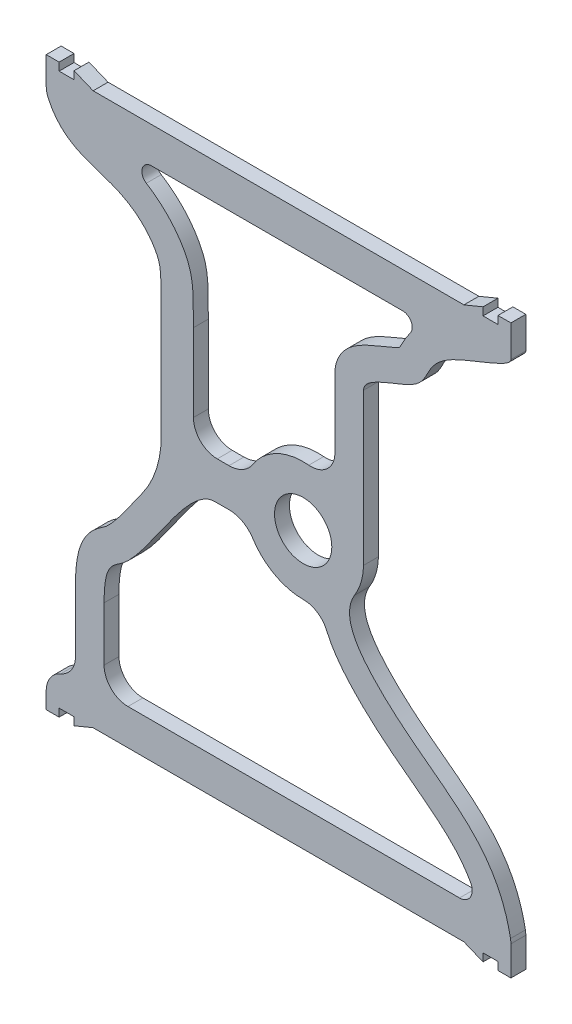
SolidWorks part; units mm, degrees
ref_plane "Front Plane" through (0, 0, 0) normal (0, 0, 1) x (1, 0, 0)
ref_plane "Top Plane" through (0, 0, 0) normal (0, 1, 0) x (1, 0, 0)
ref_plane "Right Plane" through (0, 0, 0) normal (1, 0, 0) x (0, 0, -1)
sketch "Sketch1" plane through (0, 0, 0) normal (0, 0, 1) x (1, 0, 0)
  line L0 (-41.684, 53.6194) -> (-41.684, 15.991) construction
  line L1 (-63.4451, 56.9953) -> (-61.4131, 56.1594)
  line L2 (-16.9595, 0) -> (-66.4086, 0) construction
  line L3 (-16.9595, 53.6194) -> (-16.9595, 56.9953)
  line L4 (-63.4451, 56.1594) -> (-63.4451, 56.9953)
  line L5 (-65.0326, 56.1594) -> (-65.0326, 56.9953)
  line L6 (-65.0326, 56.1594) -> (-63.4451, 56.1594)
  line L7 (-65.0326, 56.9953) -> (-66.4086, 56.9953)
  line L8 (-66.4086, 53.6194) -> (-66.4086, 56.9953)
  line L9 (-21.9549, 56.1594) -> (-61.4131, 56.1594)
  line L10 (-63.4451, -3.3759) -> (-61.4131, -2.54)
  line L11 (-19.9229, 56.1594) -> (-19.9229, 56.9953)
  line L12 (-16.9595, 53.6194) -> (-66.4086, 53.6194) construction
  line L13 (-18.3354, 56.1594) -> (-18.3354, 56.9953)
  line L14 (-18.3354, 56.1594) -> (-19.9229, 56.1594)
  line L15 (-41.684, 0) -> (-41.684, 37.6284) construction
  line L16 (-63.4451, -2.54) -> (-63.4451, -3.3759)
  line L17 (-65.0326, -2.54) -> (-63.4451, -2.54)
  line L18 (-60.2497, 9.5501) -> (-60.2497, 3.81)
  line L19 (-19.9229, 56.9953) -> (-21.9549, 56.1594)
  line L20 (-65.0326, -2.54) -> (-65.0326, -3.3759)
  line L21 (-65.0326, -3.3759) -> (-66.4086, -3.3759)
  line L22 (-39.0652, 26.8097) -> (0, 26.8097) construction
  line L23 (-66.4086, -0.809) -> (-66.4086, -3.3759)
  line L24 (0, 18.0594) -> (0, 35.56) construction
  line L25 (-21.9549, -2.54) -> (-61.4131, -2.54)
  line L26 (-19.9229, 56.1594) -> (-21.9549, 56.1594) construction
  line L27 (-19.9229, -3.3759) -> (-21.9549, -2.54)
  line L28 (-19.9229, -2.54) -> (-19.9229, -3.3759)
  line L29 (-18.3354, -2.54) -> (-19.9229, -2.54)
  line L30 (-18.3354, -2.54) -> (-18.3354, -3.3759)
  line L31 (-18.3354, -3.3759) -> (-16.9595, -3.3759)
  line L32 (-16.9595, 0) -> (-16.9595, -3.3759)
  line L33 (-54.1675, 39.6453) -> (-54.1675, 27.9353)
  line L34 (-57.7097, 1.27) -> (-22.4235, 1.27)
  line L35 (-60.2497, 52.3494) -> (-25.9826, 52.3494)
  line L36 (-63.2977, 9.5501) -> (-63.2977, 3.0525)
  line L37 (-60.2497, 9.5501) -> (-60.2497, 1.2682) construction
  line L38 (-63.2977, 9.5501) -> (-63.2977, 1.2682) construction
  line L39 (-35.6868, 43.0546) -> (-35.6868, 35.6601)
  line L40 (-18.3354, 56.9953) -> (-16.9595, 56.9953)
  line L41 (-32.6402, 42.9508) -> (-32.6402, 26.8097)
  line L43 (-35.6868, 43.0546) -> (-36.6497, 23.7188) construction
  line L44 (-32.6402, 42.9508) -> (-33.6055, 23.5672) construction
  line L47 (-46.9548, 28.8417) -> (-48.2053, 28.8417)
  line L49 (-50.7453, 31.3817) -> (-50.7453, 39.6602)
  line L51 (-46.9548, 24.7777) -> (-48.4726, 24.7777)
  line L53 (-49.6835, 24.7777) -> (-49.6835, 26.8097) construction
  line L54 (-49.6835, 26.8097) -> (-49.6835, 28.8417) construction
  arc A0 (-63.2977, 3.0525) -> (-65.121, 0.6157) centre (-65.8377, 3.0525) cw
  arc A1 (-65.121, 0.6157) -> (-66.4086, -1.4854) centre (-64.6025, -1.1472) ccw
  arc A2 (-44.4138, 23.387) -> (-39.0447, 20.4597) centre (-39.0652, 26.8097) ccw
  circle A3 centre (-39.0652, 26.8097) radius 3.048 construction
  circle A4 centre (-39.0652, 26.8097) radius 3.048
  arc A6 (-38.4663, 33.1314) -> (-44.4138, 30.2324) centre (-39.0652, 26.8097) ccw
  arc A7 (-32.6402, 26.8097) -> (-33.6055, 23.5672) centre (-38.9889, 26.9348) cw
  arc A8 (-38.4663, 33.1314) -> (-35.6868, 35.6601) centre (-38.2268, 35.6601) ccw
  arc A9 (-36.5545, 18.8205) -> (-39.0447, 20.4597) centre (-39.036, 17.7618) ccw
  arc A10 (-56.1544, 21.7299) -> (-54.1675, 27.9353) centre (-64.8512, 27.9353) ccw
  arc A11 (-57.7097, 1.27) -> (-60.2497, 3.81) centre (-57.7097, 3.81) cw
  arc A12 (-21.2407, 3.2677) -> (-22.4235, 1.27) centre (-22.4235, 2.619) cw
  arc A15 (-44.4138, 30.2324) -> (-46.9548, 28.8417) centre (-46.9548, 31.8584) cw
  arc A16 (-46.9548, 24.7777) -> (-44.4138, 23.387) centre (-46.9548, 21.761) cw
  arc A22 (-48.2053, 28.8417) -> (-50.7453, 31.3817) centre (-48.2053, 31.3817) cw
  spline S1 degree 3 poles (-66.4086, 53.6194) (-64.9241, 49.6484) (-61.0934, 49.4187) (-56.3573, 47.1016) (-54.0564, 44.0672) (-54.2181, 42.8337) (-54.1675, 39.6453) knots 0 0 0 0 0.364565 0.416182 0.697051 1 1 1 1
  spline S2 degree 3 poles (-33.6055, 23.5672) (-35.0243, 21.1781) (-27.7861, 11.0923) (-18.5237, 9.0208) (-16.9595, 0) knots 0 0 0 0 0.237026 1 1 1 1
  spline S3 degree 1 poles (-36.2261, 25.1236) (-19.9627, -0.5208) knots 0 0 1 1 construction
  spline S4 degree 3 poles (-50.7453, 39.6602) (-50.748, 39.8865) (-50.7525, 40.3577) (-50.7577, 41.1513) (-50.7634, 42.0025) (-50.7864, 42.8757) (-50.8564, 43.7423) (-51.0385, 44.6848) (-51.3706, 45.6021) (-51.751, 46.3569) (-52.4046, 47.4237) (-53.3027, 48.5258) (-54.4821, 49.5928) (-55.516, 50.3481) (-56.6891, 51.0304) (-58.0376, 51.6158) (-59.0461, 51.9498) (-59.7728, 52.1871) (-60.0872, 52.2925) (-60.2497, 52.3494) knots 0.254794 0.254794 0.254794 0.254794 0.278081 0.301369 0.347944 0.39452 0.441095 0.487671 0.534246 0.580821 0.627397 0.720548 0.767123 0.813698 0.860274 0.906849 0.953425 0.976712 1 1 1 1
  spline S6 degree 3 poles (-36.2261, 25.1236) (-36.5414, 24.5928) (-37.0422, 23.4282) (-37.2534, 21.6309) (-37.0433, 20.2118) (-36.7167, 19.1913) (-36.1284, 17.8224) (-34.9803, 16.1372) (-33.3587, 14.3655) (-31.7408, 12.8221) (-29.5831, 10.9999) (-27.0112, 9.0822) (-24.3537, 7.0375) (-22.643, 5.3519) (-21.7719, 4.1573) (-21.3521, 3.4746) (-21.1233, 3.058) (-20.7542, 2.2946) (-20.432, 1.4572) (-20.1388, 0.3851) (-20.0143, -0.2231) (-19.9627, -0.5208) knots 0 0 0 0 0.03125 0.0625 0.09375 0.111477 0.127102 0.1875 0.25 0.3125 0.375 0.5 0.625 0.75 0.811584 0.827209 0.858459 0.875 0.9375 0.96875 1 1 1 1 only from (-36.5545, 18.8205) to (-21.2407, 3.2677)
  spline S7 degree 3 poles (-48.4726, 24.7777) (-51.5001, 24.7777) (-56.6643, 13.54) (-60.2497, 13.373) (-60.2497, 9.5501) knots 0 0 0 0 0.740547 1 1 1 1
  spline S8 degree 1 poles (-48.4726, 27.8257) (-63.2977, 9.5501) knots 0 0 1 1 construction
  spline S9 degree 3 poles (-16.9595, 53.6194) (-16.9595, 52.7849) (-26.9257, 49.9354) (-24.6328, 46.056) (-32.6402, 44.3704) (-32.6402, 42.9508) knots 0 0 0 0 0.280776 0.671632 1 1 1 1
  spline S10 degree 3 poles (-48.4726, 27.8257) (-48.8211, 27.8257) (-49.5424, 27.7405) (-50.7399, 27.3407) (-51.923, 26.6109) (-53.0633, 25.5946) (-54.4165, 24.1021) (-55.4927, 22.6586) (-56.3806, 21.4129) (-56.9644, 20.585) (-57.6695, 19.5827) (-58.4649, 18.4908) (-59.0714, 17.7215) (-59.5033, 17.2266) (-59.7864, 16.9294) (-60.0317, 16.7052) (-60.1515, 16.6095) (-60.4259, 16.4243) (-60.9629, 16.0603) (-61.688, 15.4228) (-62.3751, 14.4891) (-62.8462, 13.4068) (-63.1227, 12.2668) (-63.2435, 11.2267) (-63.2901, 10.3129) (-63.2977, 9.7997) (-63.2977, 9.5501) knots 0 0 0 0 0.03125 0.0625 0.125 0.1875 0.25 0.374177 0.405427 0.4375 0.5 0.5625 0.625 0.65625 0.6875 0.71875 0.75 0.78125 0.8125 0.84375 0.875 0.90625 0.9375 0.96875 0.984375 1 1 1 1 only from (-56.1544, 21.7299) to (-63.2977, 9.5501)
  spline S12 degree 3 poles (-16.9595, 53.6194) (-16.9587, 51.7069) (-22.3477, 50.8733) (-27.9702, 48.9153) (-28.3324, 48.7786) (-32.04, 47.0588) (-34.0439, 44.0842) (-33.9777, 42.8412) (-34.0284, 39.6453) knots 0 0 0 0 0.161069 0.199423 0.36308 0.414818 0.696343 1 1 1 1 construction
  spline S13 degree 1 poles (-19.3968, 55.4497) (-35.6868, 43.0546) knots 0 0 1 1 construction
  spline S14 degree 3 poles (-19.3968, 55.4497) (-19.4767, 55.4093) (-19.6258, 55.3374) (-20.026, 55.1556) (-20.6166, 54.9064) (-21.4326, 54.5774) (-22.5957, 54.1095) (-24.0919, 53.4861) (-25.784, 52.5594) (-27.0741, 51.4872) (-27.9876, 50.3268) (-28.5015, 49.3731) (-28.7609, 48.8787) (-28.818, 48.8226) (-28.8135, 48.8158) (-28.9851, 48.704) (-29.4389, 48.4766) (-30.3255, 48.1118) (-31.4144, 47.6826) (-32.3341, 47.2703) (-33.0444, 46.905) (-33.7817, 46.4402) (-34.5599, 45.788) (-35.2236, 44.9092) (-35.5978, 43.9147) (-35.6792, 43.3371) (-35.6868, 43.0546) knots 0.089276 0.089276 0.089276 0.089276 0.103479 0.117683 0.146089 0.174496 0.202903 0.259716 0.31653 0.373343 0.430157 0.486971 0.543784 0.600598 0.657411 0.685818 0.714225 0.771038 0.827852 0.856259 0.884665 0.913072 0.941479 0.969886 0.984089 0.998292 0.998292 0.998292 0.998292 only from (-25.9826, 52.3494) to (-35.6868, 43.0546)
  point P75 (-60.2497, 1.27)
  point P82 (-39.0652, 26.8097)
  point P100 (-32.7152, 26.8097)
  point P112 (-45.0813, 24.7777)
  point P119 (-37.2317, 32.8892)
  point P126 (-50.7453, 28.8417)
  dimension "D5" = 3.048
  dimension "D6" = 0.8359
  dimension "D7" = 2.54
  dimension "D14" = 4.064
  dimension "D15" = 3.0167
  dimension "D10" = 2.54
  dimension "D11" = 2.54
  dimension "D12" = 2.54
  dimension "D2" = 1.27
  dimension "D3" = 1.376
  dimension "D4" = 2.032
  dimension "D8" = 3.048
  dimension "D9" = 3.048
extrude "Boss-Extrude2" add sketch "Sketch1" along normal blind 1.5875
fillet "Fillet1" radius 2.54 3 edges at (-66.4086, 53.6194, 0.7937) (-16.9595, 0, 0.7937) (-66.4086, -0.809, 0.7937)
fillet "Fillet2" radius 1.016 2 edges at (-60.2497, 52.3494, 0.7937) (-25.9826, 52.3494, 0.7937)
fillet "Fillet3" [suppressed] radius 2.54
